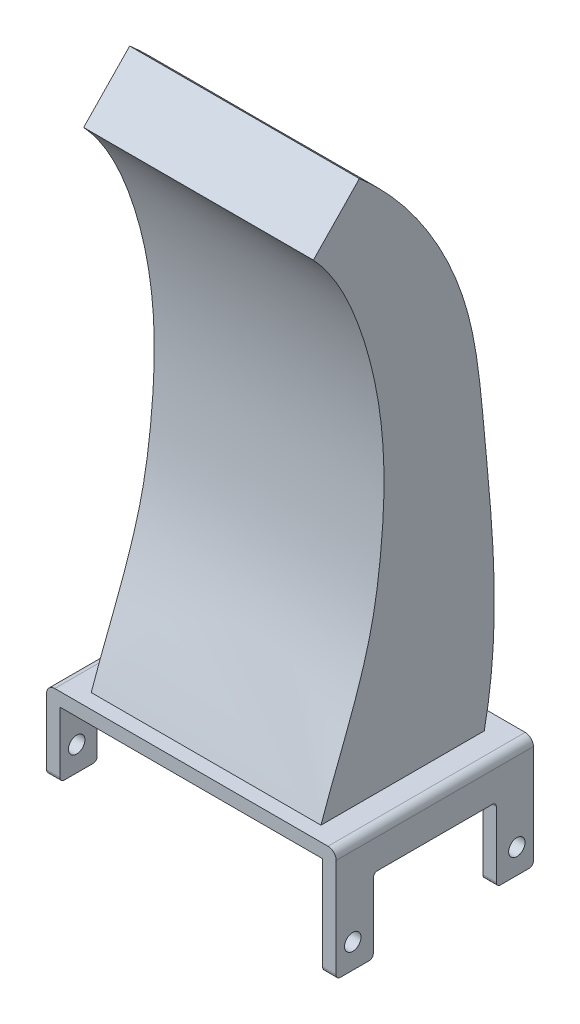
SolidWorks part; units mm, degrees
material "ABS"
ref_plane "Front Plane" through (0, 0, 0) normal (0, 0, 1) x (1, 0, 0)
ref_plane "Top Plane" through (0, 0, 0) normal (0, 1, 0) x (1, 0, 0)
ref_plane "Right Plane" through (0, 0, 0) normal (1, 0, 0) x (0, 0, -1)
sketch "Sketch1" plane through (0, 0, 0) normal (0, 1, 0) x (1, 0, 0)
  line L1 (-17.65, 12.02) -> (17.65, 12.02)
  line L2 (-17.65, 12.02) -> (-17.65, -12.02)
  line L3 (-17.65, -12.02) -> (17.65, -12.02)
  line L4 (17.65, 12.02) -> (17.65, -12.02)
  line L5 (-17.65, 12.02) -> (17.65, -12.02) construction
  line L6 (-17.65, -12.02) -> (17.65, 12.02) construction
  point P0 (0, 0)
  point P24 (0, 0)
  dimension "D1" = 35.3
  dimension "D2" = 24.04
extrude "Boss-Extrude1" add sketch "Sketch1" along normal blind 1.65
sketch "Sketch2" plane through (17.65, 0, 0) normal (1, 0, 0) x (0, 0, -1)
  line L0 (12.02, 1.65) -> (12.02, 0) construction
  line L1 (12.02, 1.65) -> (12.02, 0)
  line L2 (7.5, -11.95) -> (12.02, -11.95)
  line L3 (-12.02, 0) -> (12.02, 0)
  line L4 (-12.02, 0) -> (-12.02, -11.95)
  line L5 (-12.02, -11.95) -> (-7.5, -11.95)
  line L6 (12.02, 0) -> (12.02, -11.95)
  line L7 (-7.5, -2.95) -> (7.5, -2.95)
  line L8 (-7.5, -2.95) -> (-7.5, -11.95)
  line L10 (7.5, -2.95) -> (7.5, -11.95)
  line L11 (0, 16.4113) -> (0, -19.9375) construction
  circle A0 centre (10, -8.95) radius 1
  circle A1 centre (-10, -8.95) radius 1
  point P5 (0, -11.95)
  line M10 (-12.02, 0) -> (12.02, 0)
  dimension "D4" = 2
  dimension "D1" = 11.95
  dimension "D2" = 9
  dimension "D3" = 15
  dimension "D5" = 2.5
  dimension "D6" = 7.5
  dimension "D7" = 3
extrude "Boss-Extrude2" add sketch "Sketch2" against normal blind 1.65 contours L11 L4 L5 L8 L7 A1 M10 | L3 L11 L7 L10 L2 L6 A0
sketch "Sketch3" plane through (-17.65, 0, 0) normal (-1, 0, 0) x (0, 0, 1)
  line L0 (12.02, 1.65) -> (12.02, 0) construction
  line L1 (12.02, 1.65) -> (12.02, 0)
  line L2 (7.5, -7.95) -> (12.02, -7.95)
  line L3 (-12.02, 0) -> (12.02, 0)
  line L4 (-12.02, 0) -> (-12.02, -7.95)
  line L5 (-12.02, -7.95) -> (-7.5, -7.95)
  line L6 (12.02, 0) -> (12.02, -7.95)
  line L7 (-7.5, -2.95) -> (7.5, -2.95)
  line L8 (-7.5, -2.95) -> (-7.5, -7.95)
  line L10 (7.5, -2.95) -> (7.5, -7.95)
  line L11 (0, 3.5412) -> (0, -14.6742) construction
  circle A0 centre (10, -4.95) radius 1
  circle A1 centre (-10, -4.95) radius 1
  point P5 (0, -9.26)
  line M12 (-12.02, 0) -> (12.02, 0)
  dimension "D4" = 2
  dimension "D1" = 7.95
  dimension "D2" = 15
  dimension "D3" = 5
  dimension "D5" = 2.5
  dimension "D6" = 7.5
  dimension "D7" = 3
extrude "Boss-Extrude3" add sketch "Sketch3" against normal blind 1.65 contours L11 L4 L5 L8 L7 A1 M12 | L3 L11 L7 L10 L2 L6 A0
fillet "Fillet1" radius 1 1 edges at (17.65, 1.65, 0)
fillet "Fillet2" radius 1 1 edges at (-17.65, 1.65, 0)
fillet "Fillet3" radius 0.5 12 edges at (-16.825, -7.95, 12.02) (-16.825, -7.95, 7.5) (-16.825, -2.95, 7.5) (-16.825, -2.95, -7.5) (-16.825, -7.95, -7.5) (-16.825, -7.95, -12.02) (16.825, -11.95, -12.02) (16.825, -11.95, -7.5) (16.825, -2.95, -7.5) (16.825, -2.95, 7.5) (16.825, -11.95, 7.5) (16.825, -11.95, 12.02)
sketch "Sketch4" plane through (0, 0, 0) normal (1, 0, 0) x (0, 0, -1)
  line L0 (-12.02, 1.65) -> (12.02, 1.65) construction
  line L1 (9.6737, 1.65) -> (-10.2265, 1.65)
  line L2 (-5.5441, 67.5563) -> (-11.1514, 61.7623)
  spline S0 degree 3 poles (9.6737, 1.65) (11.8495, 12.1156) (10.1489, 27.1947) (8.1649, 50.6672) (0.6734, 62.1809) (-5.5441, 67.5563) knots 0 0 0 0 0.450088 0.646462 1 1 1 1
  spline S1 degree 3 poles (-10.2265, 1.65) (-8.8912, 5.531) (-6.3757, 11.33) (-3.8207, 19.8061) (-2.7642, 27.3684) (-2.3358, 35.5359) (-3.2038, 43.923) (-5.6021, 52.9563) (-8.5404, 58.9233) (-11.1514, 61.7623) knots 0 0 0 0 0.194994 0.300246 0.419626 0.557022 0.688203 0.818562 1 1 1 1
extrude "Boss-Extrude4" add sketch "Sketch4" along normal blind 14 and the other way blind 14 contours S0 L2 S1 L1
